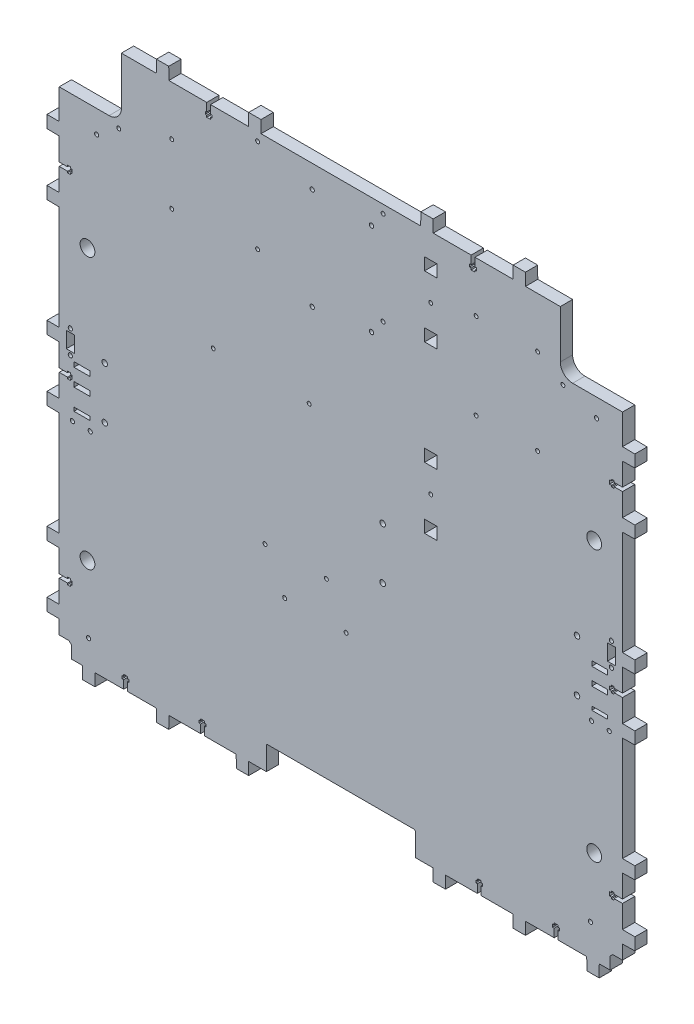
SolidWorks part; units mm, degrees
ref_plane "Front" through (0, 0, 0) normal (0, 0, 1) x (1, 0, 0)
ref_plane "Top" through (0, 0, 0) normal (0, 1, 0) x (1, 0, 0)
ref_plane "Right" through (0, 0, 0) normal (1, 0, 0) x (0, 0, -1)
sketch "Эскиз1" plane through (0, 0, 0) normal (0, 0, 1) x (1, 0, 0)
  line L0 (114.0494, -213) -> (110.9494, -213)
  line L1 (114.0494, -214.5) -> (114.0494, -213)
  line L2 (115.2494, -214.5) -> (114.0494, -214.5)
  line L3 (115.2494, -216.7) -> (115.2494, -214.5)
  line L4 (114.0494, -216.7) -> (115.2494, -216.7)
  line L5 (114.0494, -223.5) -> (114.0494, -216.7)
  line L6 (139.8994, -223.5) -> (114.0494, -223.5)
  line L7 (140.0661, -233.4986) -> (139.8994, -223.5)
  line L8 (150.0661, -233.4986) -> (140.0661, -233.4986)
  line L9 (150.0994, -223.5) -> (150.0661, -233.4986)
  line L10 (173.4494, -223.5) -> (150.0994, -223.5)
  line L11 (173.4494, -216.7) -> (173.4494, -223.5)
  line L12 (172.2494, -216.7) -> (173.4494, -216.7)
  line L13 (172.2494, -214.5) -> (172.2494, -216.7)
  line L14 (173.4494, -214.5) -> (172.2494, -214.5)
  line L15 (173.4494, -213) -> (173.4494, -214.5)
  line L16 (176.5494, -213) -> (173.4494, -213)
  line L17 (176.5494, -214.5) -> (176.5494, -213)
  line L18 (177.7494, -214.5) -> (176.5494, -214.5)
  line L19 (177.7494, -216.7) -> (177.7494, -214.5)
  line L20 (176.5494, -216.7) -> (177.7494, -216.7)
  line L21 (176.5494, -223.5) -> (176.5494, -216.7)
  line L22 (199.8994, -223.5) -> (176.5494, -223.5)
  line L23 (200.0661, -233.4986) -> (199.8994, -223.5)
  line L24 (210.0661, -233.4986) -> (200.0661, -233.4986)
  line L25 (210.0994, -223.5) -> (210.0661, -233.4986)
  line L26 (218.9994, -223.5) -> (210.0994, -223.5)
  line L27 (218.9994, -213.5) -> (218.9994, -223.5)
  line L28 (220.9994, -211.5) -> (218.9994, -213.5)
  line L29 (228.9994, -211.5) -> (220.9994, -211.5)
  line L30 (228.9994, -200.1) -> (228.9994, -211.5)
  line L31 (238.998, -199.9334) -> (228.9994, -200.1)
  line L32 (238.998, -190.0666) -> (238.998, -199.9334)
  line L33 (228.9994, -189.9) -> (238.998, -190.0666)
  line L34 (228.9994, -171.55) -> (228.9994, -189.9)
  line L35 (222.1994, -171.55) -> (228.9994, -171.55)
  line L36 (222.1994, -172.75) -> (222.1994, -171.55)
  line L37 (219.9994, -172.75) -> (222.1994, -172.75)
  line L38 (219.9994, -171.55) -> (219.9994, -172.75)
  line L39 (218.4994, -171.55) -> (219.9994, -171.55)
  line L40 (218.4994, -168.45) -> (218.4994, -171.55)
  line L41 (219.9994, -168.45) -> (218.4994, -168.45)
  line L42 (219.9994, -167.25) -> (219.9994, -168.45)
  line L43 (222.1994, -167.25) -> (219.9994, -167.25)
  line L44 (222.1994, -168.45) -> (222.1994, -167.25)
  line L45 (228.9994, -168.45) -> (222.1994, -168.45)
  line L46 (228.9994, -150.1) -> (228.9994, -168.45)
  line L47 (238.998, -149.9334) -> (228.9994, -150.1)
  line L48 (238.998, -140.0666) -> (238.998, -149.9334)
  line L49 (228.9994, -139.9) -> (238.998, -140.0666)
  line L50 (238.998, 90.0666) -> (228.9994, 89.9)
  line L51 (238.998, 99.9334) -> (238.998, 90.0666)
  line L52 (228.9994, 100.1) -> (238.998, 99.9334)
  line L53 (228.9994, 118.45) -> (228.9994, 100.1)
  line L54 (222.1994, 118.45) -> (228.9994, 118.45)
  line L55 (222.1994, 117.25) -> (222.1994, 118.45)
  line L56 (219.9994, 117.25) -> (222.1994, 117.25)
  line L57 (219.9994, 118.45) -> (219.9994, 117.25)
  line L58 (218.4994, 118.45) -> (219.9994, 118.45)
  line L59 (218.4994, 121.55) -> (218.4994, 118.45)
  line L60 (219.9994, 121.55) -> (218.4994, 121.55)
  line L61 (219.9994, 122.75) -> (219.9994, 121.55)
  line L62 (222.1994, 122.75) -> (219.9994, 122.75)
  line L63 (222.1994, 121.55) -> (222.1994, 122.75)
  line L64 (228.9994, 121.55) -> (222.1994, 121.55)
  line L65 (228.9994, 139.9) -> (228.9994, 121.55)
  line L66 (238.998, 140.0666) -> (228.9994, 139.9)
  line L67 (238.998, 149.9334) -> (238.998, 140.0666)
  line L68 (228.9994, 150.1) -> (238.998, 149.9334)
  line L69 (228.9994, 174.5) -> (228.9994, 150.1)
  line L70 (150.0994, 223.5) -> (178.4494, 223.5)
  line L71 (150.0661, 233.4986) -> (150.0994, 223.5)
  line L72 (140.0661, 233.4986) -> (150.0661, 233.4986)
  line L73 (139.8994, 223.5) -> (140.0661, 233.4986)
  line L74 (109.0494, 223.5) -> (139.8994, 223.5)
  line L75 (109.0494, 216.7) -> (109.0494, 223.5)
  line L76 (110.2494, 216.7) -> (109.0494, 216.7)
  line L77 (110.2494, 214.5) -> (110.2494, 216.7)
  line L78 (109.0494, 214.5) -> (110.2494, 214.5)
  line L79 (109.0494, 213) -> (109.0494, 214.5)
  line L80 (105.9494, 213) -> (109.0494, 213)
  line L81 (105.9494, 214.5) -> (105.9494, 213)
  line L82 (104.7494, 214.5) -> (105.9494, 214.5)
  line L83 (104.7494, 216.7) -> (104.7494, 214.5)
  line L84 (105.9494, 216.7) -> (104.7494, 216.7)
  line L85 (105.9494, 223.5) -> (105.9494, 216.7)
  line L86 (75.0994, 223.5) -> (105.9494, 223.5)
  line L87 (75.0661, 233.4986) -> (75.0994, 223.5)
  line L88 (65.0661, 233.4986) -> (75.0661, 233.4986)
  line L89 (64.8994, 223.5) -> (65.0661, 233.4986)
  line L90 (-64.9006, 223.5) -> (64.8994, 223.5)
  line L91 (-64.9339, 233.4986) -> (-64.9006, 223.5)
  line L92 (-74.9339, 233.4986) -> (-64.9339, 233.4986)
  line L93 (-75.1006, 223.5) -> (-74.9339, 233.4986)
  line L94 (-105.9506, 223.5) -> (-75.1006, 223.5)
  line L95 (-105.9506, 216.7) -> (-105.9506, 223.5)
  line L96 (-104.7506, 216.7) -> (-105.9506, 216.7)
  line L97 (-104.7506, 214.5) -> (-104.7506, 216.7)
  line L98 (-105.9506, 214.5) -> (-104.7506, 214.5)
  line L99 (-105.9506, 213) -> (-105.9506, 214.5)
  line L100 (-109.0506, 213) -> (-105.9506, 213)
  line L101 (-109.0506, 214.5) -> (-109.0506, 213)
  line L102 (-110.2506, 214.5) -> (-109.0506, 214.5)
  line L103 (-110.2506, 216.7) -> (-110.2506, 214.5)
  line L104 (-109.0506, 216.7) -> (-110.2506, 216.7)
  line L105 (-109.0506, 223.5) -> (-109.0506, 216.7)
  line L106 (-139.9006, 223.5) -> (-109.0506, 223.5)
  line L107 (-139.9339, 233.4986) -> (-139.9006, 223.5)
  line L108 (-149.9339, 233.4986) -> (-139.9339, 233.4986)
  line L109 (-150.1006, 223.5) -> (-149.9339, 233.4986)
  line L110 (-178.4506, 223.5) -> (-150.1006, 223.5)
  line L111 (-229.0006, 150.1) -> (-229.0006, 174.5)
  line L112 (-238.9992, 150.0666) -> (-229.0006, 150.1)
  line L113 (-238.9992, 140.0666) -> (-238.9992, 150.0666)
  line L114 (-229.0006, 139.9) -> (-238.9992, 140.0666)
  line L115 (-229.0006, 121.55) -> (-229.0006, 139.9)
  line L116 (-222.2006, 121.55) -> (-229.0006, 121.55)
  line L117 (-222.2006, 122.75) -> (-222.2006, 121.55)
  line L118 (-220.0006, 122.75) -> (-222.2006, 122.75)
  line L119 (-220.0006, 121.55) -> (-220.0006, 122.75)
  line L120 (-218.5006, 121.55) -> (-220.0006, 121.55)
  line L121 (-218.5006, 118.45) -> (-218.5006, 121.55)
  line L122 (-220.0006, 118.45) -> (-218.5006, 118.45)
  line L123 (-220.0006, 117.25) -> (-220.0006, 118.45)
  line L124 (-222.2006, 117.25) -> (-220.0006, 117.25)
  line L125 (-222.2006, 118.45) -> (-222.2006, 117.25)
  line L126 (-229.0006, 118.45) -> (-222.2006, 118.45)
  line L127 (-229.0006, 100.1) -> (-229.0006, 118.45)
  line L128 (-238.9992, 100.0666) -> (-229.0006, 100.1)
  line L129 (-238.9992, 90.0666) -> (-238.9992, 100.0666)
  line L130 (-229.0006, 89.9) -> (-238.9992, 90.0666)
  line L131 (-238.9992, -139.9334) -> (-229.0006, -139.9)
  line L132 (-238.9992, -149.9334) -> (-238.9992, -139.9334)
  line L133 (-229.0006, -150.1) -> (-238.9992, -149.9334)
  line L134 (-229.0006, -168.45) -> (-229.0006, -150.1)
  line L135 (-222.2006, -168.45) -> (-229.0006, -168.45)
  line L136 (-222.2006, -167.25) -> (-222.2006, -168.45)
  line L137 (-220.0006, -167.25) -> (-222.2006, -167.25)
  line L138 (-220.0006, -168.45) -> (-220.0006, -167.25)
  line L139 (-218.5006, -168.45) -> (-220.0006, -168.45)
  line L140 (-218.5006, -171.55) -> (-218.5006, -168.45)
  line L141 (-220.0006, -171.55) -> (-218.5006, -171.55)
  line L142 (-220.0006, -172.75) -> (-220.0006, -171.55)
  line L143 (-222.2006, -172.75) -> (-220.0006, -172.75)
  line L144 (-222.2006, -171.55) -> (-222.2006, -172.75)
  line L145 (-229.0006, -171.55) -> (-222.2006, -171.55)
  line L146 (-229.0006, -189.9) -> (-229.0006, -171.55)
  line L147 (-238.9992, -189.9334) -> (-229.0006, -189.9)
  line L148 (-238.9992, -199.9334) -> (-238.9992, -189.9334)
  line L149 (-229.0006, -200.1) -> (-238.9992, -199.9334)
  line L150 (-229.0006, -211.5) -> (-229.0006, -200.1)
  line L151 (-221.0006, -211.5) -> (-229.0006, -211.5)
  line L152 (-219.0006, -213.5) -> (-221.0006, -211.5)
  line L153 (-219.0006, -223.5) -> (-219.0006, -213.5)
  line L154 (-210.1006, -223.5) -> (-219.0006, -223.5)
  line L155 (-209.9339, -233.4986) -> (-210.1006, -223.5)
  line L156 (-199.9339, -233.4986) -> (-209.9339, -233.4986)
  line L157 (-199.9006, -223.5) -> (-199.9339, -233.4986)
  line L158 (-176.5506, -223.5) -> (-199.9006, -223.5)
  line L159 (-176.5506, -216.7) -> (-176.5506, -223.5)
  line L160 (-177.7506, -216.7) -> (-176.5506, -216.7)
  line L161 (-177.7506, -214.5) -> (-177.7506, -216.7)
  line L162 (-176.5506, -214.5) -> (-177.7506, -214.5)
  line L163 (-176.5506, -213) -> (-176.5506, -214.5)
  line L164 (-173.4506, -213) -> (-176.5506, -213)
  line L165 (-173.4506, -214.5) -> (-173.4506, -213)
  line L166 (-172.2506, -214.5) -> (-173.4506, -214.5)
  line L167 (-172.2506, -216.7) -> (-172.2506, -214.5)
  line L168 (-173.4506, -216.7) -> (-172.2506, -216.7)
  line L169 (-173.4506, -223.5) -> (-173.4506, -216.7)
  line L170 (-150.1006, -223.5) -> (-173.4506, -223.5)
  line L171 (-149.9339, -233.4986) -> (-150.1006, -223.5)
  line L172 (-139.9339, -233.4986) -> (-149.9339, -233.4986)
  line L173 (-139.9006, -223.5) -> (-139.9339, -233.4986)
  line L174 (-114.0506, -223.5) -> (-139.9006, -223.5)
  line L175 (-114.0506, -216.7) -> (-114.0506, -223.5)
  line L176 (-115.2506, -216.7) -> (-114.0506, -216.7)
  line L177 (-115.2506, -214.5) -> (-115.2506, -216.7)
  line L178 (-114.0506, -214.5) -> (-115.2506, -214.5)
  line L179 (-114.0506, -213) -> (-114.0506, -214.5)
  line L180 (-110.9506, -213) -> (-114.0506, -213)
  line L181 (-110.9506, -214.5) -> (-110.9506, -213)
  line L182 (-109.7506, -214.5) -> (-110.9506, -214.5)
  line L183 (-109.7506, -216.7) -> (-109.7506, -214.5)
  line L184 (-110.9506, -216.7) -> (-109.7506, -216.7)
  line L185 (-110.9506, -223.5) -> (-110.9506, -216.7)
  line L186 (-85.1006, -223.5) -> (-110.9506, -223.5)
  line L187 (-84.9339, -233.4986) -> (-85.1006, -223.5)
  line L188 (-74.9339, -233.4986) -> (-84.9339, -233.4986)
  line L189 (-74.9006, -223.5) -> (-74.9339, -233.4986)
  line L190 (75.0661, -233.4986) -> (74.8994, -223.5)
  line L191 (85.0661, -233.4986) -> (75.0661, -233.4986)
  line L192 (85.0994, -223.5) -> (85.0661, -233.4986)
  line L193 (110.9494, -223.5) -> (85.0994, -223.5)
  line L194 (110.9494, -216.7) -> (110.9494, -223.5)
  line L195 (109.7494, -216.7) -> (110.9494, -216.7)
  line L196 (109.7494, -214.5) -> (109.7494, -216.7)
  line L197 (110.9494, -214.5) -> (109.7494, -214.5)
  line L198 (110.9494, -213) -> (110.9494, -214.5)
  line L199 (188.4494, 174.5) -> (228.9994, 174.5)
  line L200 (178.4494, 184.5) -> (178.4494, 223.5)
  line L201 (-178.4506, 184.5) -> (-178.4506, 223.5)
  line L202 (-229.0006, 174.5) -> (-188.4506, 174.5)
  line L203 (216.6994, -7.0618) -> (216.6994, 5.9382)
  line L204 (216.6994, 5.9382) -> (223.1994, 5.9382)
  line L205 (223.1994, 5.9382) -> (223.1994, -7.0618)
  line L206 (223.1994, -7.0618) -> (216.6994, -7.0618)
  line L207 (217.0053, -17) -> (204.0053, -17)
  line L208 (204.0053, -17) -> (204.0053, -13)
  line L209 (204.0053, -13) -> (217.0053, -13)
  line L210 (217.0053, -13) -> (217.0053, -17)
  line L211 (204.0053, -31) -> (217.0053, -31)
  line L212 (204.0053, -45) -> (217.0053, -45)
  line L213 (217.0053, -45) -> (217.0053, -48)
  line L214 (217.0053, -48) -> (204.0053, -48)
  line L215 (204.0053, -48) -> (204.0053, -45)
  line L216 (-216.7006, -7.0618) -> (-216.7006, 5.9382)
  line L217 (-216.7006, 5.9382) -> (-223.2006, 5.9382)
  line L218 (-223.2006, 5.9382) -> (-223.2006, -7.0618)
  line L219 (-223.2006, -7.0618) -> (-216.7006, -7.0618)
  line L220 (-217.0064, -17) -> (-204.0064, -17)
  line L221 (-204.0064, -17) -> (-204.0064, -13)
  line L222 (-204.0064, -13) -> (-217.0064, -13)
  line L223 (-217.0064, -13) -> (-217.0064, -17)
  line L224 (-204.0064, -31) -> (-217.0064, -31)
  line L225 (-204.0064, -45) -> (-217.0064, -45)
  line L226 (-217.0064, -45) -> (-217.0064, -48)
  line L227 (-217.0064, -48) -> (-204.0064, -48)
  line L228 (-204.0064, -48) -> (-204.0064, -45)
  line L229 (-229.0006, 89.9) -> (-229.0006, 5.1)
  line L230 (-238.9992, 5.0666) -> (-229.0006, 5.1)
  line L231 (-238.9992, -4.9334) -> (-238.9992, 5.0666)
  line L232 (-229.0006, -5.1) -> (-238.9992, -4.9334)
  line L233 (-229.0006, -23.45) -> (-229.0006, -5.1)
  line L234 (-222.2006, -23.45) -> (-229.0006, -23.45)
  line L235 (-222.2006, -22.25) -> (-222.2006, -23.45)
  line L236 (-220.0006, -22.25) -> (-222.2006, -22.25)
  line L237 (-220.0006, -23.45) -> (-220.0006, -22.25)
  line L238 (-220.0006, -27.75) -> (-220.0006, -26.55)
  line L239 (-222.2006, -27.75) -> (-220.0006, -27.75)
  line L240 (-222.2006, -26.55) -> (-222.2006, -27.75)
  line L241 (-229.0006, -26.55) -> (-222.2006, -26.55)
  line L242 (-229.0006, -44.9) -> (-229.0006, -26.55)
  line L243 (-238.9992, -44.9334) -> (-229.0006, -44.9)
  line L244 (-238.9992, -54.9334) -> (-238.9992, -44.9334)
  line L245 (-229.0006, -55.1) -> (-238.9992, -54.9334)
  line L246 (228.9994, 89.9) -> (228.9994, 5.1)
  line L247 (238.998, -54.9334) -> (228.9994, -55.1)
  line L248 (238.998, -45.0666) -> (238.998, -54.9334)
  line L249 (228.9994, -44.9) -> (238.998, -45.0666)
  line L250 (228.9994, -26.55) -> (228.9994, -44.9)
  line L251 (222.1994, -26.55) -> (228.9994, -26.55)
  line L252 (222.1994, -27.75) -> (222.1994, -26.55)
  line L253 (219.9994, -27.75) -> (222.1994, -27.75)
  line L254 (219.9994, -26.55) -> (219.9994, -27.75)
  line L255 (219.9994, -22.25) -> (219.9994, -23.45)
  line L256 (222.1994, -22.25) -> (219.9994, -22.25)
  line L257 (222.1994, -23.45) -> (222.1994, -22.25)
  line L258 (228.9994, -23.45) -> (222.1994, -23.45)
  line L259 (228.9994, -5.1) -> (228.9994, -23.45)
  line L260 (238.9992, -5.0286) -> (228.9994, -5.1)
  line L261 (238.998, 4.9334) -> (238.9992, -5.0286)
  line L262 (228.9994, 5.1) -> (238.998, 4.9334)
  line L263 (228.9994, -139.9) -> (228.9994, -55.1)
  line L264 (-229.0006, -139.9) -> (-229.0006, -55.1)
  line L265 (68.0494, 193.4) -> (68.0494, 203.4)
  line L266 (68.0494, 203.4) -> (78.1494, 203.4)
  line L267 (78.1494, 203.4) -> (78.1494, 193.4)
  line L268 (78.1494, 193.4) -> (68.0494, 193.4)
  line L269 (68.0494, 143.4) -> (68.0494, 153.4)
  line L270 (68.0494, 153.4) -> (78.1494, 153.4)
  line L271 (78.1494, 153.4) -> (78.1494, 143.4)
  line L272 (78.1494, 143.4) -> (68.0494, 143.4)
  line L273 (68.0494, 58.6) -> (68.0494, 68.6)
  line L274 (68.0494, 68.6) -> (78.1494, 68.6)
  line L275 (78.1494, 68.6) -> (78.1494, 58.6)
  line L276 (78.1494, 58.6) -> (68.0494, 58.6)
  line L277 (68.0494, 8.6) -> (68.0494, 18.6)
  line L278 (68.0494, 18.6) -> (78.1494, 18.6)
  line L279 (78.1494, 18.6) -> (78.1494, 8.6)
  line L280 (78.1494, 8.6) -> (68.0494, 8.6)
  line L281 (219.9994, -23.45) -> (218.4994, -23.45)
  line L282 (218.4994, -23.45) -> (218.4994, -26.55)
  line L283 (218.4994, -26.55) -> (219.9994, -26.55)
  line L284 (-220.0006, -23.45) -> (-218.5006, -23.45)
  line L285 (-218.5006, -23.45) -> (-218.5006, -26.55)
  line L286 (-218.5006, -26.55) -> (-220.0006, -26.55)
  line L287 (-204.0064, -31) -> (-204.0064, -27)
  line L288 (-204.0064, -27) -> (-217.0064, -27)
  line L289 (-217.0064, -27) -> (-217.0064, -31)
  line L290 (217.0053, -31) -> (217.0053, -27)
  line L291 (217.0053, -27) -> (204.0053, -27)
  line L292 (204.0053, -27) -> (204.0053, -31)
  line L293 (60.4994, -223.5) -> (60.4994, -205)
  line L294 (59.4994, -204) -> (-59.5006, -204)
  line L295 (-60.5006, -205) -> (-60.5006, -223.5)
  line L296 (-74.9006, -223.5) -> (-60.5006, -223.5)
  line L297 (60.4994, -223.5) -> (74.8994, -223.5)
  circle A0 centre (-25.7579, 52.9507) radius 1.6
  arc A1 (178.4494, 184.5) -> (188.4494, 174.5) centre (188.4494, 184.5) ccw
  arc A2 (-188.4506, 174.5) -> (-178.4506, 184.5) centre (-188.4506, 184.5) ccw
  circle A3 centre (-205.1517, -201.7518) radius 1.7
  circle A4 centre (-198.5933, 156.116) radius 1.7
  circle A5 centre (207.8844, 159.5442) radius 1.7
  circle A6 centre (202.9113, -197.5011) radius 1.7
  circle A7 centre (180.5494, 169.4) radius 1.6
  circle A8 centre (-180.5506, 169.4) radius 1.6
  circle A9 centre (-137.5159, 134.3541) radius 1.6
  circle A10 centre (-137.5159, 183.3541) radius 1.6
  circle A11 centre (4.2134, -93.3236) radius 1.6
  circle A12 centre (-11.7866, -63.3236) radius 1.6
  circle A13 centre (-103.7579, 52.9507) radius 1.6
  circle A14 centre (-23.2859, 122.4835) radius 1.75
  circle A15 centre (-23.2859, 205.0335) radius 1.75
  circle A16 centre (24.9741, 128.8335) radius 1.75
  circle A17 centre (24.9741, 203.7635) radius 1.75
  circle A18 centre (34.3187, 140.7933) radius 1.6
  circle A19 centre (34.3187, 216.7933) radius 1.6
  circle A20 centre (-67.6813, 140.7933) radius 1.6
  circle A21 centre (-67.6813, 216.7933) radius 1.6
  circle A22 centre (205.9994, 72.5) radius 6
  circle A23 centre (205.9994, -147.5) radius 6
  circle A24 centre (219.9494, -10.0618) radius 1.7
  circle A25 centre (219.9494, 8.9382) radius 1.7
  circle A26 centre (218.2053, -55.4875) radius 1.7
  circle A27 centre (203.8053, -55.4875) radius 1.7
  circle A28 centre (-206.0006, 72.5) radius 6
  circle A29 centre (-206.0006, -147.5) radius 6
  circle A30 centre (-219.9506, -10.0618) radius 1.7
  circle A31 centre (-219.9506, 8.9382) radius 1.7
  circle A32 centre (-218.2064, -55.4875) radius 1.7
  circle A33 centre (-203.8064, -55.4875) radius 1.7
  circle A34 centre (192.0053, -43.5) radius 2.25
  circle A35 centre (192.0053, -1.5) radius 2.25
  circle A36 centre (-192.0064, -43.5) radius 2.25
  circle A37 centre (-192.0064, -1.5) radius 2.25
  circle A38 centre (73.0994, 173.4) radius 1.6
  circle A39 centre (73.0994, 38.6) radius 1.6
  circle A40 centre (34.0053, -43.5) radius 2.25
  circle A41 centre (34.0053, -1.5) radius 2.25
  circle A42 centre (-45.6544, -93.8541) radius 1.6
  circle A43 centre (-61.6544, -63.8541) radius 1.6
  circle A44 centre (159.9808, 112.5336) radius 1.6
  circle A45 centre (159.9808, 182.5336) radius 1.6
  circle A46 centre (109.9808, 112.5336) radius 1.6
  circle A47 centre (109.9808, 182.5336) radius 1.6
  arc A48 (-59.5006, -204) -> (-60.5006, -205) centre (-59.5006, -205) ccw
  arc A49 (60.4994, -205) -> (59.4994, -204) centre (59.4994, -205) ccw
  point P24 (0, 0)
  point P399 (0, 0)
  point P400 (0, 0)
extrude "Бобышка-Вытянуть1" add sketch "Эскиз1" along normal blind 10
